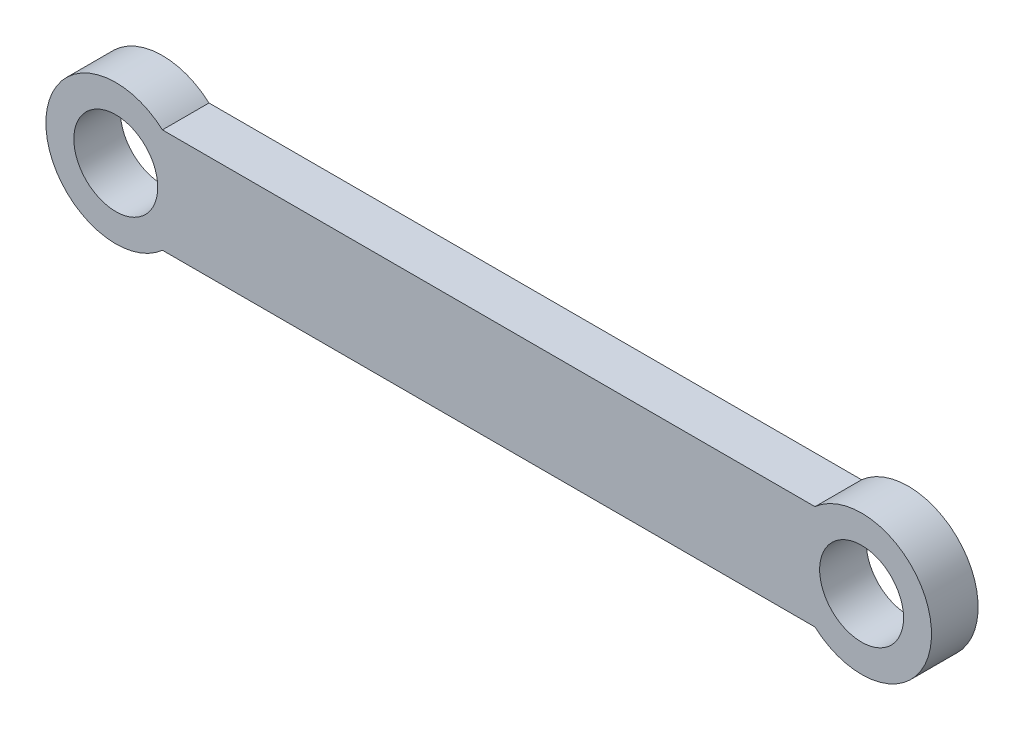
SolidWorks part; units mm, degrees
ref_plane "Front" through (0, 0, 0) normal (0, 0, 1) x (1, 0, 0)
ref_plane "Top" through (0, 0, 0) normal (0, 1, 0) x (1, 0, 0)
ref_plane "Right" through (0, 0, 0) normal (1, 0, 0) x (0, 0, -1)
sketch "스케치1" plane through (0, 0, 0) normal (0, 0, 1) x (1, 0, 0)
  line L0 (5, 5.5902) -> (75, 5.5902)
  line L1 (80, 0) -> (0, 0) construction
  line L2 (5, -5.5902) -> (75, -5.5902)
  circle A0 centre (0, 0) radius 4.5
  arc A1 (5, 5.5902) -> (5, -5.5902) centre (0, 0) ccw
  circle A2 centre (80, 0) radius 4.5
  arc A3 (75, -5.5902) -> (75, 5.5902) centre (80, 0) ccw
  dimension "D1" = 9
  dimension "D2" = 15
  dimension "D4" = 9
  dimension "D5" = 15
  dimension "D3" = 70
  dimension "D6" = 80
extrude "보스-돌출1" add sketch "스케치1" along normal blind 5
